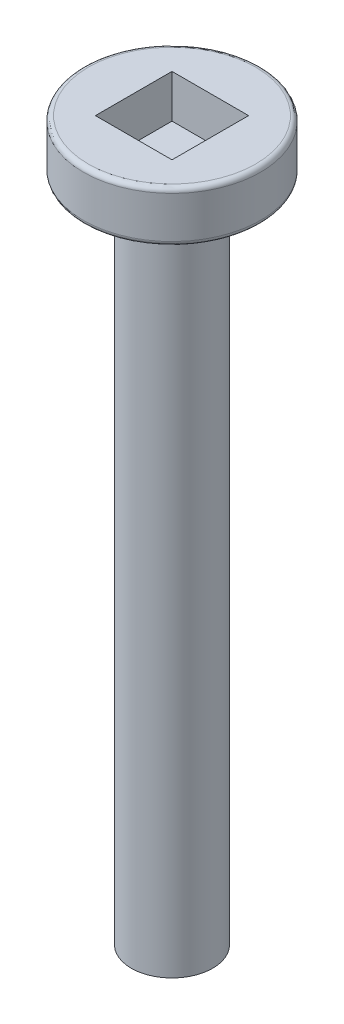
SolidWorks part; units mm, degrees
ref_plane "Front Plane" through (0, 0, 0) normal (0, 0, 1) x (1, 0, 0)
ref_plane "Top Plane" through (0, 0, 0) normal (0, 1, 0) x (1, 0, 0)
ref_plane "Right Plane" through (0, 0, 0) normal (1, 0, 0) x (0, 0, -1)
sketch "Sketch1" plane through (0, 0, 0) normal (0, 1, 0) x (1, 0, 0)
  circle A0 centre (0, 0) radius 4.699
  dimension "D1" = 9.398
extrude "Boss-Extrude1" add sketch "Sketch1" against normal blind 2.7178
sketch "Sketch2" plane through (0, 0, 0) normal (0, 1, 0) x (1, 0, 0)
  circle A0 centre (0, 0) radius 2.159
  dimension "D1" = 4.318
extrude "Boss-Extrude2" add sketch "Sketch2" against normal blind 38.1
sketch "Sketch3" plane through (0, 0, 0) normal (0, 1, 0) x (1, 0, 0)
  line L1 (-2.032, 2.032) -> (2.032, 2.032)
  line L2 (-2.032, 2.032) -> (-2.032, -2.032)
  line L3 (-2.032, -2.032) -> (2.032, -2.032)
  line L4 (2.032, 2.032) -> (2.032, -2.032)
  dimension "D1" = 4.064
  dimension "D2" = 4.064
  dimension "D3" = 2.032
  dimension "D4" = 2.032
extrude "Cut-Extrude1" cut sketch "Sketch3" against normal blind 2.286
fillet "Fillet2" radius 0.254 2 edges at (0, -2.7178, 4.699) (0, 0, 4.699)
